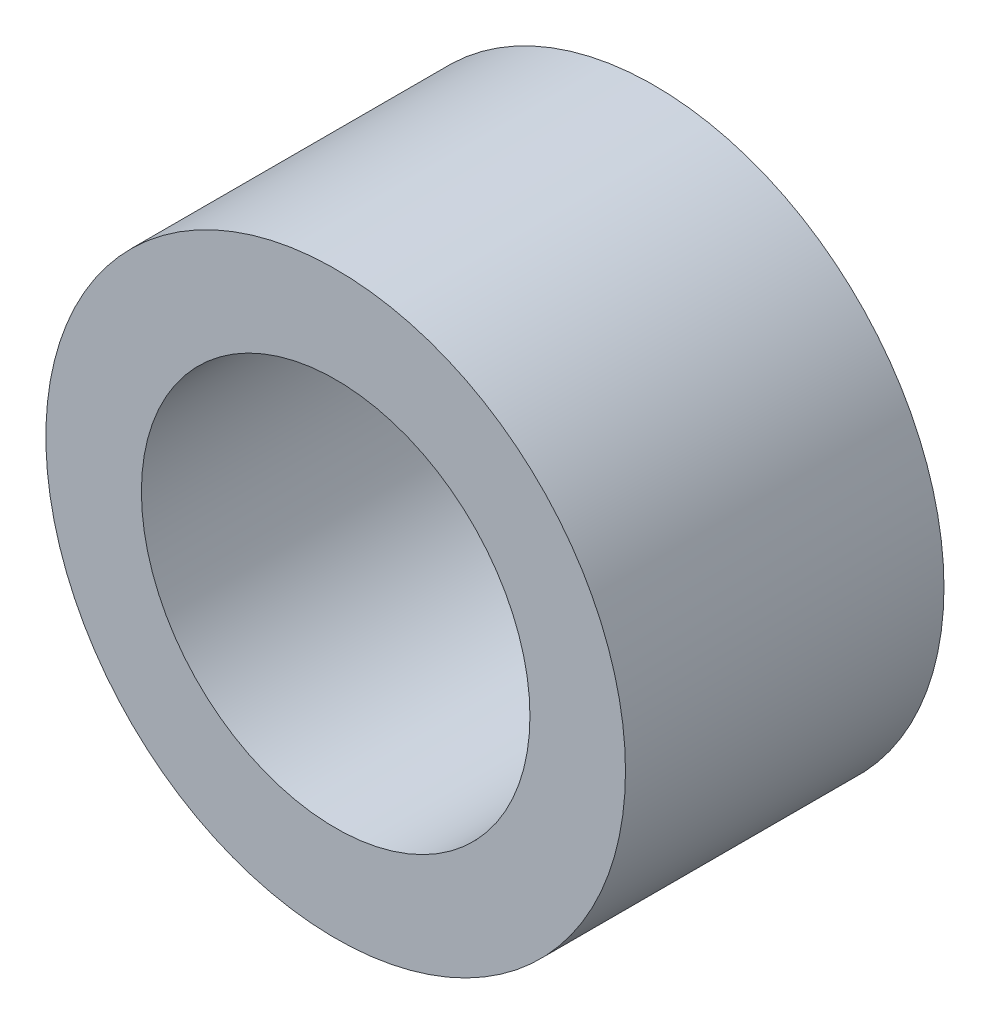
SolidWorks part; units mm, degrees
ref_plane "Alzado" through (0, 0, 0) normal (0, 0, 1) x (1, 0, 0)
ref_plane "Planta" through (0, 0, 0) normal (0, 1, 0) x (1, 0, 0)
ref_plane "Vista lateral" through (0, 0, 0) normal (1, 0, 0) x (0, 0, -1)
sketch "Croquis1" plane through (0, 0, 0) normal (0, 0, 1) x (1, 0, 0)
  circle A0 centre (0, 0) radius 6.1
  circle A1 centre (0, 0) radius 9.1
  dimension "D1" = 12.2
  dimension "D2" = 3
extrude "Saliente-Extruir1" add sketch "Croquis1" along normal blind 10
